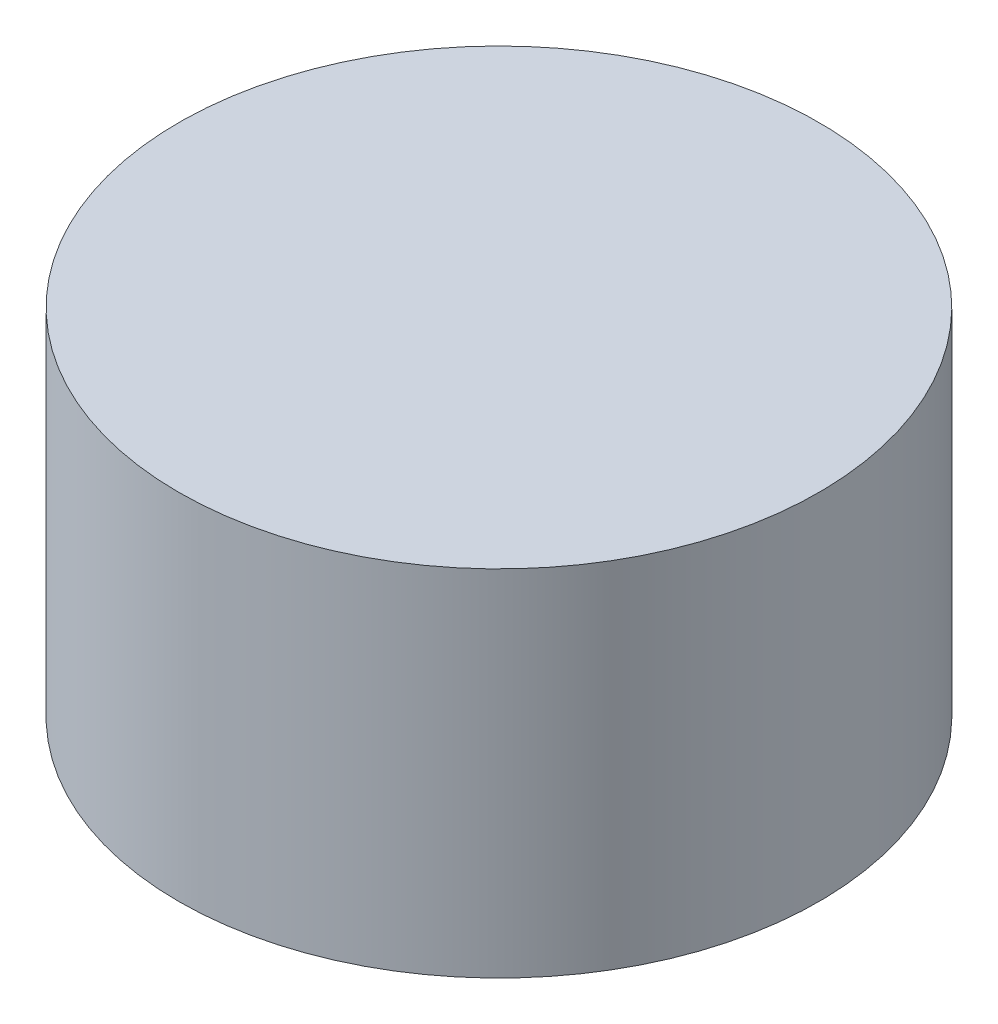
SolidWorks part; units mm, degrees
material "ABS"
ref_plane "Front Plane" through (0, 0, 0) normal (0, 0, 1) x (1, 0, 0)
ref_plane "Top Plane" through (0, 0, 0) normal (0, 1, 0) x (1, 0, 0)
ref_plane "Right Plane" through (0, 0, 0) normal (1, 0, 0) x (0, 0, -1)
sketch "Sketch1" plane through (0, 0, 0) normal (0, 1, 0) x (1, 0, 0)
  circle A0 centre (0, 0) radius 10.925
  dimension "D1" = 21.85
extrude "Boss-Extrude1" add sketch "Sketch1" along normal blind 12.09
